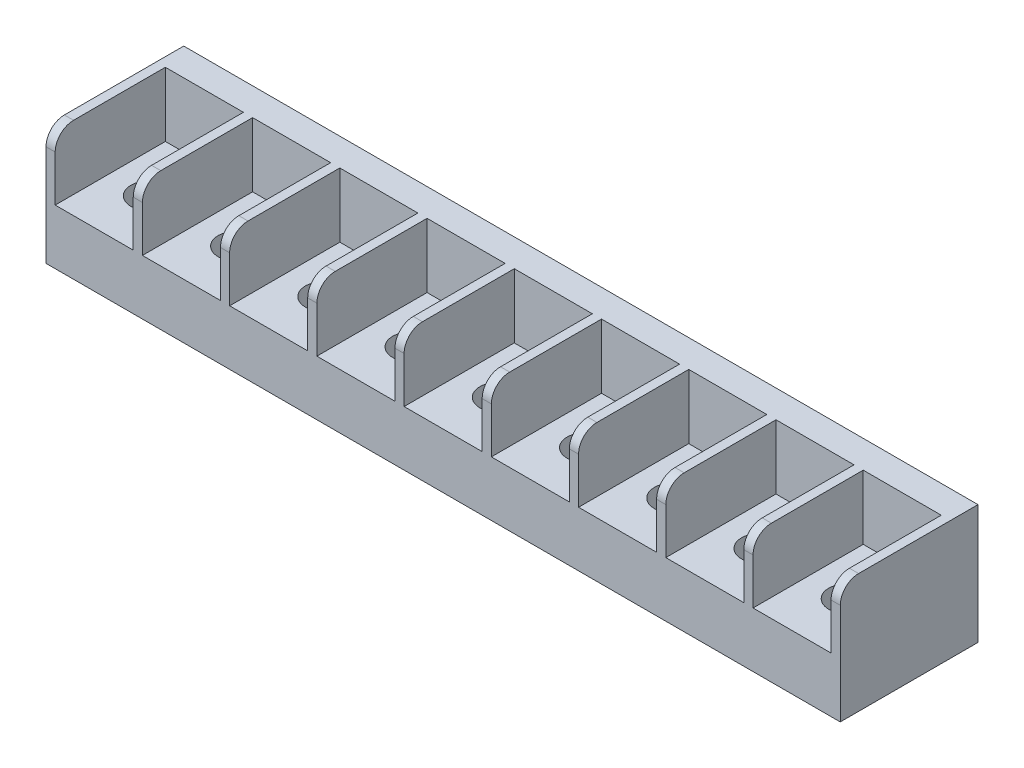
SolidWorks part; units mm, degrees
material "ABS"
ref_plane "前视基准面" through (0, 0, 0) normal (0, 0, 1) x (1, 0, 0)
ref_plane "上视基准面" through (0, 0, 0) normal (0, 1, 0) x (1, 0, 0)
ref_plane "右视基准面" through (0, 0, 0) normal (1, 0, 0) x (0, 0, -1)
sketch "Sketch2" plane through (0, 0, 0) normal (0, 1, 0) x (1, 0, 0)
  line L0 (0, 12) -> (86.5, 12)
  line L1 (0, 0) -> (86.5, 0)
  line L2 (0, 0) -> (0, 15)
  line L3 (0, 15) -> (86.5, 15)
  line L4 (86.5, 0) -> (86.5, 15)
  line L5 (10.5, 12) -> (19, 12)
  line L6 (1, 12) -> (9.5, 12)
  line L7 (1, 12) -> (1, 0)
  line L8 (1, 0) -> (9.5, 0)
  line L9 (9.5, 12) -> (9.5, 0)
  line L10 (10.5, 12) -> (10.5, 0)
  line L11 (10.5, 0) -> (19, 0)
  line L12 (19, 12) -> (19, 0)
  line L13 (20, 12) -> (28.5, 12)
  line L14 (20, 12) -> (20, 0)
  line L15 (20, 0) -> (28.5, 0)
  line L16 (28.5, 12) -> (28.5, 0)
  line L17 (29.5, 12) -> (38, 12)
  line L18 (29.5, 12) -> (29.5, 0)
  line L19 (29.5, 0) -> (38, 0)
  line L20 (38, 12) -> (38, 0)
  line L21 (39, 12) -> (47.5, 12)
  line L22 (39, 12) -> (39, 0)
  line L23 (39, 0) -> (47.5, 0)
  line L24 (47.5, 12) -> (47.5, 0)
  line L25 (48.5, 12) -> (57, 12)
  line L26 (48.5, 12) -> (48.5, 0)
  line L27 (48.5, 0) -> (57, 0)
  line L28 (57, 12) -> (57, 0)
  line L29 (58, 12) -> (66.5, 12)
  line L30 (58, 12) -> (58, 0)
  line L31 (58, 0) -> (66.5, 0)
  line L32 (66.5, 12) -> (66.5, 0)
  line L33 (67.5, 12) -> (76, 12)
  line L34 (67.5, 12) -> (67.5, 0)
  line L35 (67.5, 0) -> (76, 0)
  line L36 (76, 12) -> (76, 0)
  line L37 (77, 12) -> (85.5, 12)
  line L38 (77, 12) -> (77, 0)
  line L39 (77, 0) -> (85.5, 0)
  line L40 (85.5, 12) -> (85.5, 0)
  line L41 (86.5, 6) -> (0, 6) construction
  dimension "D1" = 86.5
  dimension "D2" = 15
  dimension "D3" = 3
  dimension "D4" = 1
  dimension "D5" = 8.5
  dimension "D7" = 6
  dimension "D8" = 10.5
  dimension "D6" = 9
sketch "Sketch3" plane through (0, 0, 0) normal (0, 1, 0) x (1, 0, 0)
  line L1 (0, 0) -> (86.5, 0)
  line L20 (0, 0) -> (86.5, 0)
  line L21 (86.5, 0) -> (86.5, 15)
  line L22 (86.5, 15) -> (0, 15)
  line L23 (0, 15) -> (0, 0)
  line L25 (86.5, 0) -> (86.5, 15)
  line L26 (86.5, 15) -> (0, 15)
  line L27 (0, 15) -> (0, 0)
  dimension "D3" = 0
extrude "Boss-Extrude1" add sketch "Sketch3" along normal blind 13
sketch "Sketch4" plane through (0, 13, 0) normal (0, 1, 0) x (1, 0, 0)
  line L4 (9.5, 12) -> (1, 12)
  line L5 (9.5, 0) -> (9.5, 12)
  line L6 (1, 0) -> (9.5, 0)
  line L7 (1, 12) -> (1, 0)
  line L8 (9.5, 12) -> (1, 12)
  line L9 (9.5, 0) -> (9.5, 12)
  line L10 (1, 0) -> (9.5, 0)
  line L11 (1, 12) -> (1, 0)
  dimension "D1" = 0
extrude "Cut-Extrude1" cut sketch "Sketch4" against normal blind 7
pattern_linear "LPattern1" count 9 spacing 9.5 along (1, 0, 0) of "Cut-Extrude1"
fillet "Fillet1" radius 2 10 edges at (67, 13, 0) (76.5, 13, 0) (86, 13, 0) (57.5, 13, 0) (48, 13, 0) (38.5, 13, 0) (29, 13, 0) (19.5, 13, 0) (10, 13, 0) (0.5, 13, 0)
sketch "Sketch5" plane through (0, 6, 0) normal (0, 1, 0) x (1, 0, 0)
  line L0 (1, 12) -> (1, 0) construction
  circle A0 centre (5.25, 6) radius 2
  dimension "D2" = 4
  dimension "D3" = 4.25
  dimension "D4" = 6
extrude "Cut-Extrude2" cut sketch "Sketch5" against normal through all
pattern_linear "LPattern2" count 9 spacing 9.5 along (1, 0, 0) of "Cut-Extrude2"
